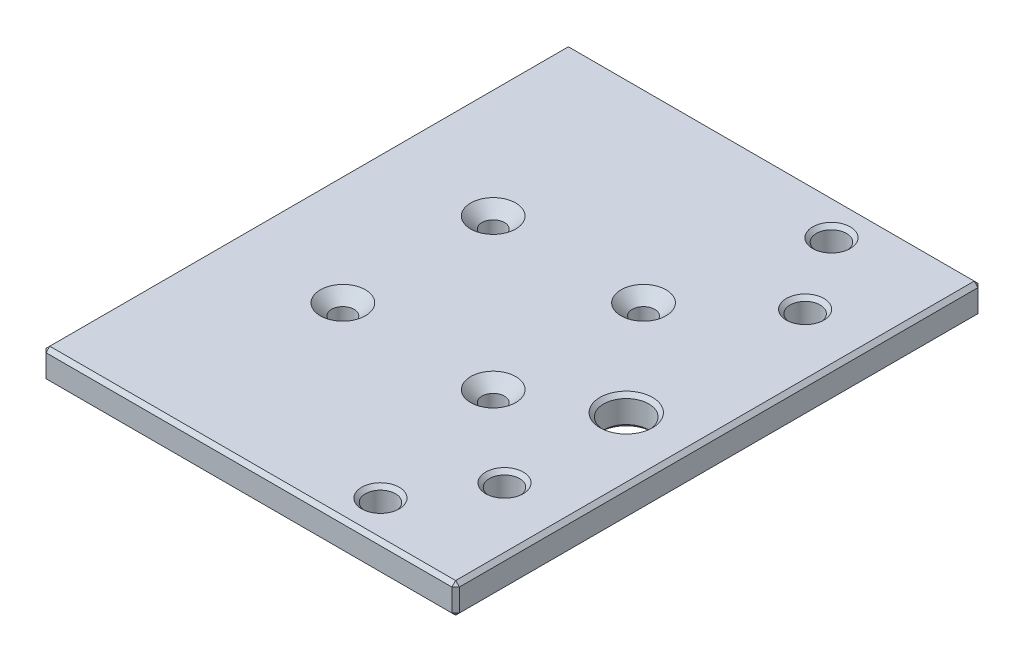
SolidWorks part; units mm, degrees
ref_plane "Alzado" through (0, 0, 0) normal (0, 0, 1) x (1, 0, 0)
ref_plane "Planta" through (0, 0, 0) normal (0, 1, 0) x (1, 0, 0)
ref_plane "Vista lateral" through (0, 0, 0) normal (1, 0, 0) x (0, 0, -1)
sketch "Croquis1" plane through (0, 0, 0) normal (0, 1, 0) x (1, 0, 0)
  line L1 (-8.019, 36.2785) -> (46.981, 36.2785)
  line L2 (-8.019, 36.2785) -> (-8.019, -33.7215)
  line L3 (-8.019, -33.7215) -> (46.981, -33.7215)
  line L4 (46.981, 36.2785) -> (46.981, -33.7215)
  circle A0 centre (6.981, 11.2785) radius 1.5
  circle A1 centre (26.981, 11.2785) radius 1.5
  circle A2 centre (6.981, -8.7215) radius 1.5
  circle A3 centre (26.981, -8.7215) radius 1.5
  circle A4 centre (31.981, 31.2785) radius 2
  circle A5 centre (31.981, -28.7215) radius 2
  circle A6 centre (38.481, -18.7215) radius 2
  circle A7 centre (38.481, -2.5215) radius 3
  circle A8 centre (38.481, 21.2785) radius 2
  point P24 (45.3763, -8.7409)
  dimension "D7" = 3
  dimension "D8" = 4
  dimension "D9" = 4
  dimension "D10" = 3
  dimension "D11" = 3
  dimension "D12" = 3
  dimension "D17" = 4
  dimension "D18" = 6
  dimension "D19" = 4
  dimension "D1" = 70
  dimension "D2" = 15
  dimension "D3" = 20
  dimension "D4" = 20
  dimension "D5" = 25
  dimension "D6" = 20
  dimension "D13" = 40
  dimension "D14" = 5
  dimension "D15" = 5
  dimension "D16" = 8.5
  dimension "D20" = 15
  dimension "D21" = 16.2
  dimension "D22" = 23.8
extrude "Saliente-Extruir1" add sketch "Croquis1" along normal blind 4
chamfer "Chaflán1" distance 0.5 angle 45 26 edges at (26.981, 0, 10.2215) (26.981, 0, -9.7785) (6.981, 0, -9.7785) (6.981, 0, 10.2215) (-8.019, 2, -36.2785) (-8.019, 2, 33.7215) (46.981, 2, 33.7215) (19.481, 0, 33.7215) (46.981, 0, -1.2785) (-8.019, 0, -1.2785) (19.481, 0, -36.2785) (46.981, 2, -36.2785) (19.481, 4, -36.2785) (46.981, 4, -1.2785) (19.481, 4, 33.7215) (-8.019, 4, -1.2785) (31.981, 0, 30.7215) (31.981, 0, -29.2785) (31.981, 4, 30.7215) (31.981, 4, -29.2785) (38.481, 0, -19.2785) (38.481, 0, 20.7215) (38.481, 0, 5.5215) (38.481, 4, 20.7215) (38.481, 4, 5.5215) (38.481, 4, -19.2785)
chamfer "Chaflán2" distance 1.5 angle 45 4 edges at (26.981, 4, 10.2215) (6.981, 4, 10.2215) (26.981, 4, -9.7785) (6.981, 4, -9.7785)
